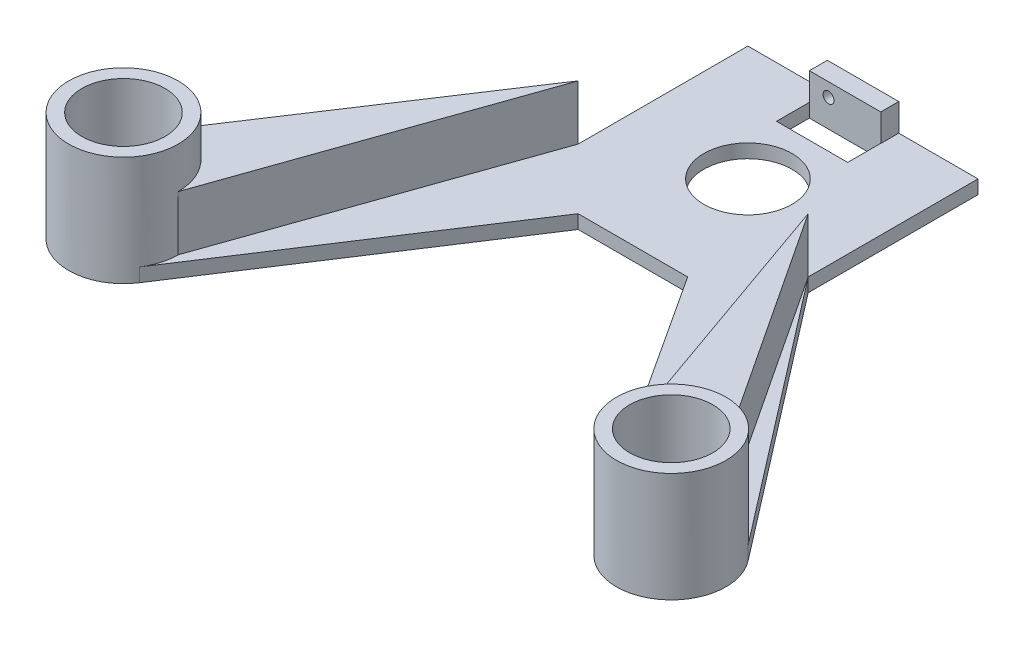
SolidWorks part; units mm, degrees
ref_plane "前视基准面" through (0, 0, 0) normal (0, 0, 1) x (1, 0, 0)
ref_plane "上视基准面" through (0, 0, 0) normal (0, 1, 0) x (1, 0, 0)
ref_plane "右视基准面" through (0, 0, 0) normal (1, 0, 0) x (0, 0, -1)
sketch "草图6" plane through (0, 0, 0) normal (0, 1, 0) x (1, 0, 0)
  line L1 (-21, -21) -> (21, -21)
  line L2 (-21, -21) -> (-21, 21)
  line L3 (-21, 21) -> (21, 21)
  line L4 (21, -21) -> (21, 21)
  line L5 (0, 21) -> (0, -21) construction
  line L6 (-21, 0) -> (21, 0) construction
  circle A0 centre (0, 0) radius 8.05
  point P0 (0, 0)
  dimension "D1" = 16.1
extrude "凸台-拉伸1" add sketch "草图6" along normal blind 2.5
sketch "草图7" plane through (0, 2.5, 0) normal (0, 1, 0) x (1, 0, 0)
  line L3 (-21, -10) -> (-57.92, -57.8948)
  line L7 (-10, -21) -> (-41.6253, -69.4648)
  line L8 (10, -21) -> (41.6253, -69.4648)
  line L9 (21, -10) -> (57.92, -57.8948)
  circle A4 centre (-50, -64) radius 4.05
  circle A5 centre (50, -64) radius 4.05
  arc A6 (-57.92, -57.8948) -> (-41.6253, -69.4648) centre (-50, -64) ccw
  arc A7 (41.6253, -69.4648) -> (57.92, -57.8948) centre (50, -64) ccw
  dimension "D3" = 8.1
  dimension "D4" = 8.1
  dimension "D5" = 20
  dimension "D6" = 20
extrude "凸台-拉伸5" add sketch "草图7" against normal blind 2.5
sketch "草图9" plane through (0, 0, 0) normal (0, -1, 0) x (-1, 0, 0)
  circle A0 centre (50, -64) radius 7.6
  circle A1 centre (50, -64) radius 10
  circle A2 centre (-50, -64) radius 7.6
  circle A3 centre (-50, -64) radius 10
extrude "凸台-拉伸7" add sketch "草图9" against normal blind 20
sketch "草图10" plane through (0, 2.5, 0) normal (0, 1, 0) x (1, 0, 0)
  line L0 (-50, -54) -> (-21, -10)
  line L1 (-21, -10) -> (-40, -64)
  line L2 (21, -10) -> (40, -64)
  line L3 (21, -10) -> (50, -54)
  circle A0 centre (-50, -64) radius 10 construction
  arc A1 (-41.6253, -69.4648) -> (-57.92, -57.8948) centre (-50, -64) ccw construction
  circle A2 centre (50, -64) radius 10 construction
  arc A3 (57.92, -57.8948) -> (41.6253, -69.4648) centre (50, -64) ccw construction
  arc A4 (-40, -64) -> (-50, -54) centre (-50, -64) ccw
  arc A5 (50, -54) -> (40, -64) centre (50, -64) ccw
extrude "凸台-拉伸8" add sketch "草图10" along normal blind 10
sketch "草图11" plane through (0, 0, 0) normal (0, -1, 0) x (-1, 0, 0)
  line L1 (-6.5, 17.7149) -> (6.5, 17.7149)
  line L2 (-6.5, 17.7149) -> (-6.5, 11.7149)
  line L3 (-6.5, 11.7149) -> (6.5, 11.7149)
  line L4 (6.5, 17.7149) -> (6.5, 11.7149)
  line L5 (-6.5, 17.7149) -> (6.5, 11.7149) construction
  line L6 (-6.5, 11.7149) -> (6.5, 17.7149) construction
  point P0 (0, 14.7149)
  dimension "D1" = 13
  dimension "D2" = 6
extrude "切除-拉伸1" cut sketch "草图11" against normal blind 10
sketch "草图12" plane through (0, 2.5, 0) normal (0, 1, 0) x (1, 0, 0)
  line L0 (21, 21) -> (-21, 21) construction
  line L1 (-6.5, 17.7149) -> (6.5331, 17.7149)
  line L2 (-6.5, 17.7149) -> (-6.5, 21)
  line L3 (-6.5, 21) -> (6.5331, 21)
  line L4 (6.5331, 17.7149) -> (6.5331, 21)
extrude "凸台-拉伸9" add sketch "草图12" along normal blind 5
sketch "草图13" plane through (0, 0, -17.7149) normal (0, 0, 1) x (1, 0, 0)
  circle A0 centre (-2.9958, 5.0237) radius 1
extrude "切除-拉伸2" cut sketch "草图13" against normal blind 10
